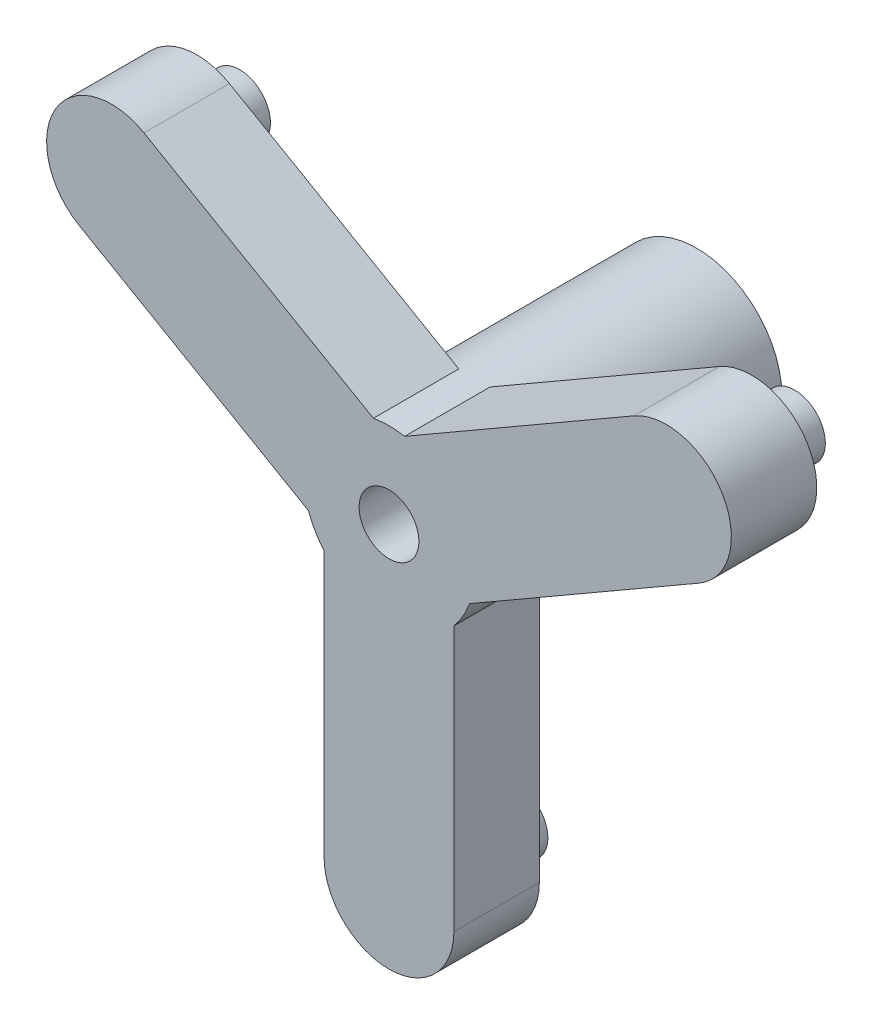
SolidWorks part; units mm, degrees
ref_plane "Front" through (0, 0, 0) normal (0, 0, 1) x (1, 0, 0)
ref_plane "Top" through (0, 0, 0) normal (0, 1, 0) x (1, 0, 0)
ref_plane "Right" through (0, 0, 0) normal (1, 0, 0) x (0, 0, -1)
sketch "Sketch1" plane through (0, 0, 0) normal (0, 0, 1) x (1, 0, 0)
  circle A0 centre (0, 0) radius 6.35
  dimension "D1" = 12.7
extrude "Boss-Extrude1" add sketch "Sketch1" along normal blind 16.51
sketch "Sketch4" plane through (0, 0, 16.51) normal (0, 0, 1) x (1, 0, 0)
  line L0 (0, 0) -> (0, -23.8125) construction
  line L1 (-4.826, -23.8125) -> (-4.826, -4.127)
  line L2 (4.826, -23.8125) -> (4.826, -4.127)
  line L3 (18.2092, 16.0857) -> (1.1611, 6.2429)
  line L4 (23.0352, 7.7268) -> (5.9871, -2.1159)
  line L5 (0, 0) -> (20.6222, 11.9062) construction
  line L6 (-23.0352, 7.7268) -> (-5.9871, -2.1159)
  line L7 (-18.2092, 16.0857) -> (-1.1611, 6.2429)
  line L8 (0, 0) -> (-20.6222, 11.9063) construction
  circle A0 centre (0, -23.8125) radius 2.286
  arc A1 (-4.826, -23.8125) -> (4.826, -23.8125) centre (0, -23.8125) ccw
  circle A2 centre (0, -23.8125) radius 4.826 construction
  circle A3 centre (20.6222, 11.9062) radius 2.286
  arc A4 (23.0352, 7.7268) -> (18.2092, 16.0857) centre (20.6222, 11.9062) ccw
  circle A5 centre (-20.6222, 11.9063) radius 2.286
  arc A6 (-18.2092, 16.0857) -> (-23.0352, 7.7268) centre (-20.6222, 11.9063) ccw
  circle A7 centre (0, 0) radius 6.35 construction
  circle A8 centre (0, 0) radius 6.35
  point P27 (0, 0)
  circle M4 centre (0, 0) radius 6.35
  dimension "D2" = 4.572
  dimension "D1" = 23.8125
  dimension "D3" = 2.54
  dimension "D4" = 3
extrude "Boss-Extrude4" add sketch "Sketch4" along normal blind 6.35 contours A0 | A5 | A3 | L7 L6 L1 L2 L4 L3 M4 | L1 A1 L2 A0 M4 | L4 A4 L3 A3 M4 | L7 A6 L6 A5 M4
sketch "Sketch6" plane through (0, 0, 16.51) normal (0, 0, -1) x (-1, 0, 0)
  line L0 (0, 0) -> (0, -23.8125) construction
  circle A0 centre (0, -23.8125) radius 2.286
  circle A1 centre (-20.6222, 11.9063) radius 2.286
  circle A2 centre (20.6222, 11.9062) radius 2.286
  point P10 (0, 0)
  dimension "D2" = 4.572
  dimension "D1" = 23.8125
  dimension "D3" = 3
extrude "Boss-Extrude5" add sketch "Sketch6" along normal blind 3.175
sketch "Sketch7" plane through (0, 0, 0) normal (0, 0, -1) x (-1, 0, 0)
  circle A0 centre (0, 0) radius 2.2225
  dimension "D1" = 4.445
extrude "Cut-Extrude1" cut sketch "Sketch7" against normal through all contours A0
